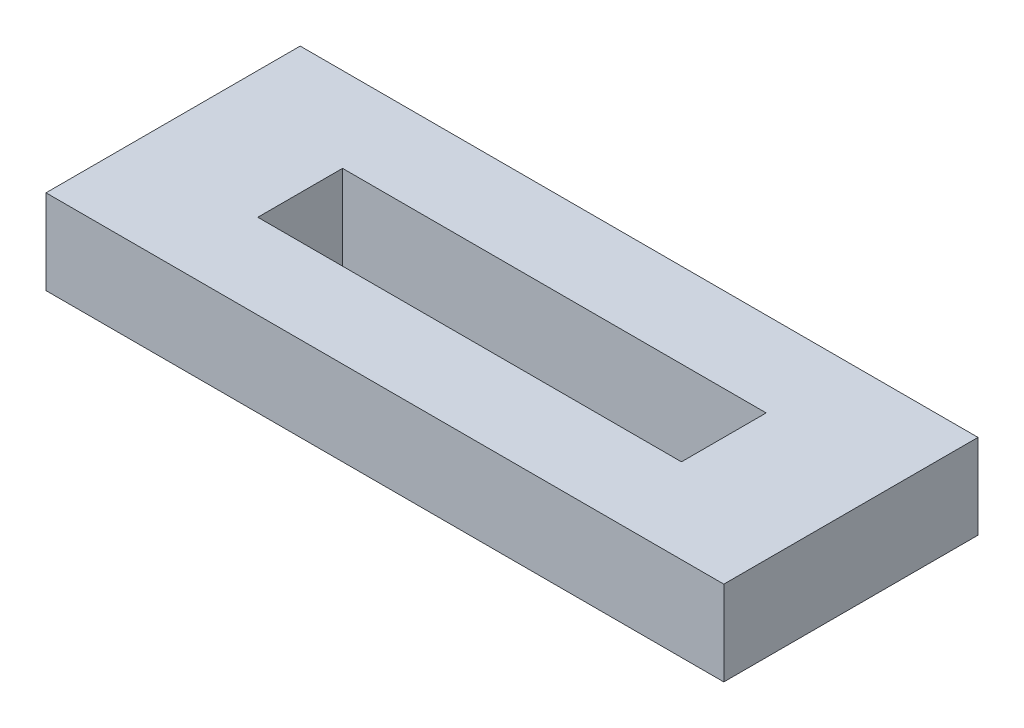
SolidWorks part; units mm, degrees
ref_plane "Front Plane" through (0, 0, 0) normal (0, 0, 1) x (1, 0, 0)
ref_plane "Top Plane" through (0, 0, 0) normal (0, 1, 0) x (1, 0, 0)
ref_plane "Right Plane" through (0, 0, 0) normal (1, 0, 0) x (0, 0, -1)
sketch "Sketch1" plane through (0, 0, 0) normal (0, 1, 0) x (1, 0, 0)
  line L1 (40, -15) -> (-40, -15)
  line L2 (40, -15) -> (40, 15)
  line L3 (40, 15) -> (-40, 15)
  line L4 (-40, -15) -> (-40, 15)
  line L5 (40, -15) -> (-40, 15) construction
  line L6 (40, 15) -> (-40, -15) construction
  line L7 (25, -5) -> (-25, -5)
  line L8 (25, -5) -> (25, 5)
  line L9 (25, 5) -> (-25, 5)
  line L10 (-25, -5) -> (-25, 5)
  line L11 (25, -5) -> (-25, 5) construction
  line L12 (25, 5) -> (-25, -5) construction
  point P0 (0, 0)
  point P6 (0, 0)
  dimension "D1" = 30
  dimension "D2" = 80
  dimension "D3" = 10
  dimension "D4" = 50
extrude "Boss-Extrude1" add sketch "Sketch1" along normal blind 10
